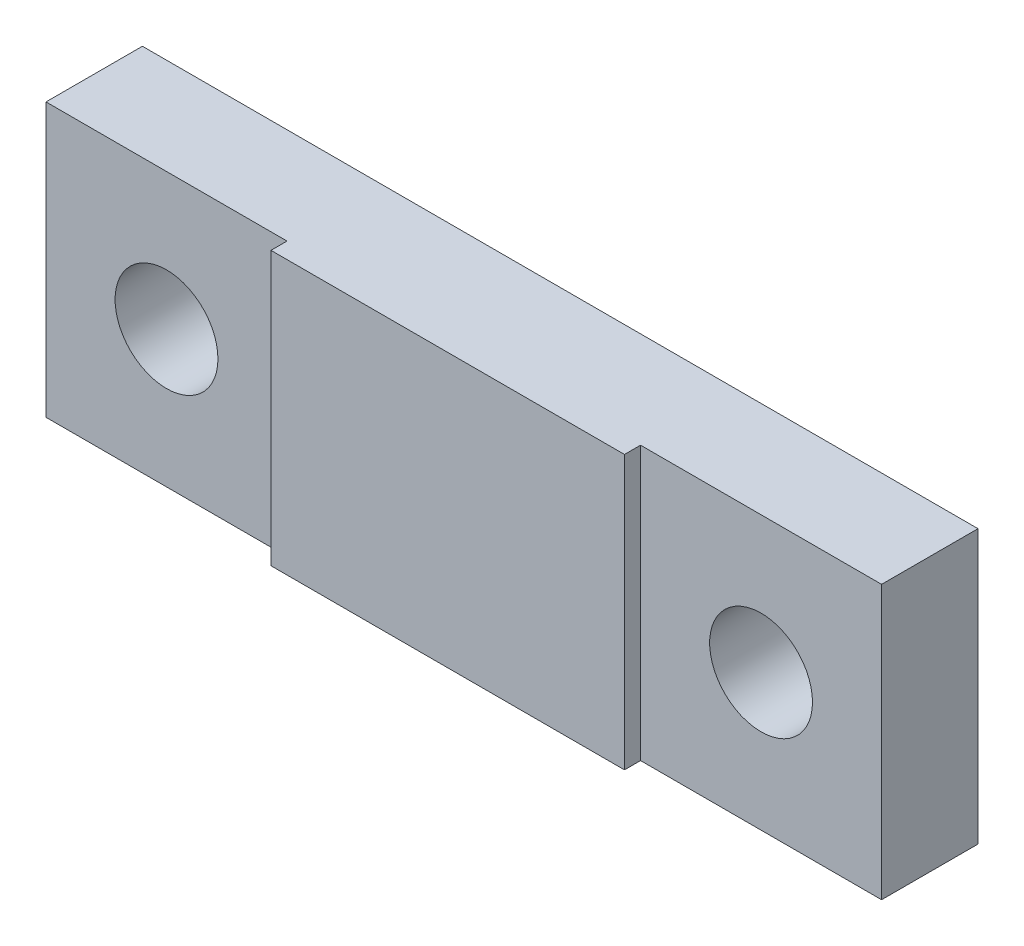
SolidWorks part; units mm, degrees
ref_plane "Plan de face" through (0, 0, 0) normal (0, 0, 1) x (1, 0, 0)
ref_plane "Plan de dessus" through (0, 0, 0) normal (0, 1, 0) x (1, 0, 0)
ref_plane "Plan de droite" through (0, 0, 0) normal (1, 0, 0) x (0, 0, -1)
sketch "Esquisse1" plane through (0, 0, 0) normal (0, 0, 1) x (1, 0, 0)
  line L1 (0, 0) -> (26, 0)
  line L2 (0, 0) -> (0, -8.5)
  line L3 (0, -8.5) -> (26, -8.5)
  line L4 (26, 0) -> (26, -8.5)
  circle A0 centre (3.75, -4.25) radius 1.6
  circle A1 centre (22.25, -4.25) radius 1.6
  point P10 (0, -4.25)
  point P13 (26, -4.25)
  dimension "D1" = 3.2
  dimension "D2" = 3.2
  dimension "D3" = 18.5
  dimension "D4" = 3.75
  dimension "D5" = 3.75
  dimension "D6" = 8.5
extrude "Boss.-Extru.1" add sketch "Esquisse1" along normal blind 3
sketch "Esquisse2" plane through (0, 0, 3) normal (0, 0, 1) x (1, 0, 0)
  line L0 (0, -8.5) -> (26, -8.5) construction
  line L1 (18.5, -8.5) -> (7.5, -8.5)
  line L2 (18.5, -8.5) -> (18.5, 0)
  line L3 (18.5, 0) -> (7.5, 0)
  line L4 (7.5, -8.5) -> (7.5, 0)
  line L5 (26, 0) -> (0, 0) construction
  point P8 (13, -8.5)
  dimension "D1" = 11
extrude "Boss.-Extru.2" add sketch "Esquisse2" along normal blind 0.5
